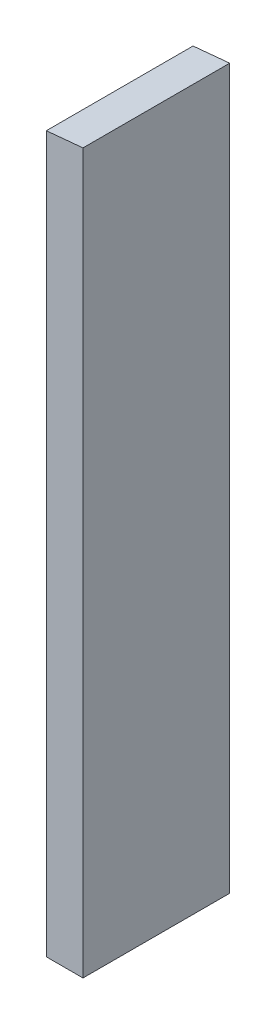
SolidWorks part; units mm, degrees
ref_plane "Front Plane" through (0, 0, 0) normal (0, 0, 1) x (1, 0, 0)
ref_plane "Top Plane" through (0, 0, 0) normal (0, 1, 0) x (1, 0, 0)
ref_plane "Right Plane" through (0, 0, 0) normal (1, 0, 0) x (0, 0, -1)
sketch "Sketch1" plane through (0, 0, 0) normal (0, 0, 1) x (1, 0, 0)
  line L1 (0, 0) -> (6.35, 0)
  line L2 (0, 0) -> (0, 123.8597)
  line L3 (0, 123.8597) -> (6.35, 124.46)
  line L4 (6.35, 0) -> (6.35, 124.46)
  dimension "D1" = 6.35
  dimension "D2" = 124.46
  dimension "D3" = 5.4
extrude "Boss-Extrude1" add sketch "Sketch1" along normal blind 25.4
